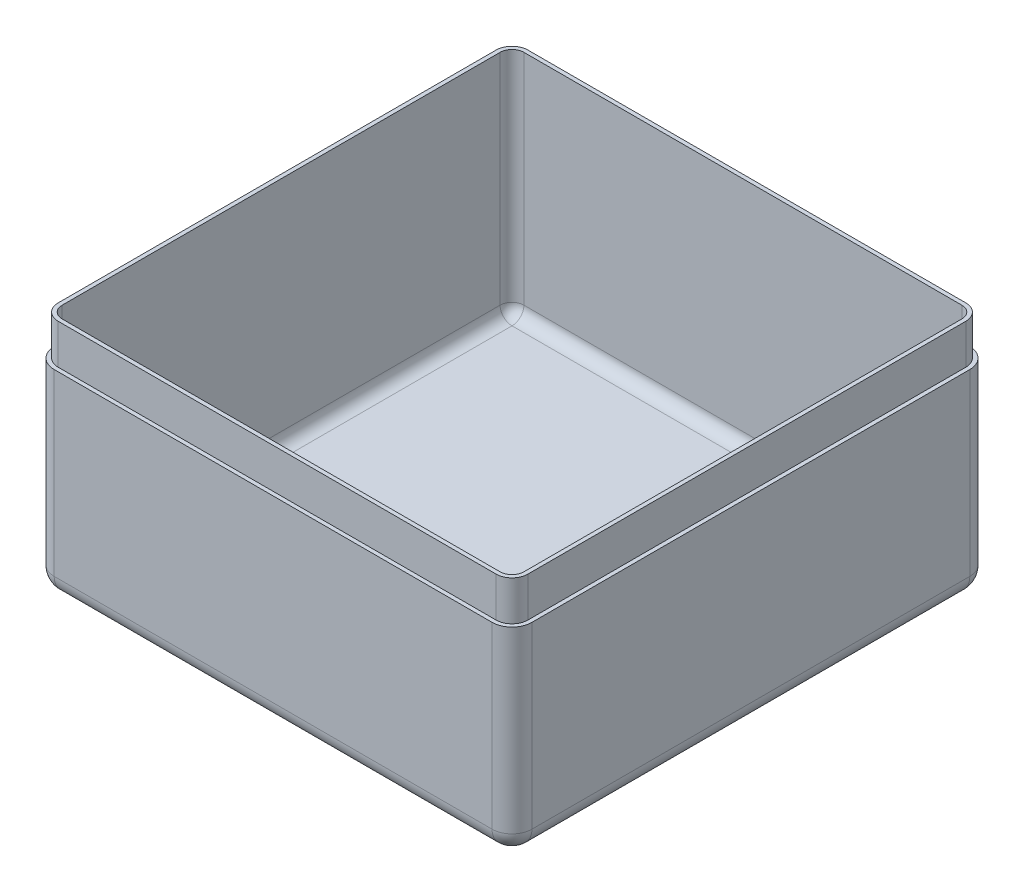
SolidWorks part; units mm, degrees
ref_plane "Front" through (0, 0, 0) normal (0, 0, 1) x (1, 0, 0)
ref_plane "Top" through (0, 0, 0) normal (0, 1, 0) x (1, 0, 0)
ref_plane "Right" through (0, 0, 0) normal (1, 0, 0) x (0, 0, -1)
sketch "Sketch1" plane through (0, 0, 0) normal (0, 1, 0) x (1, 0, 0)
  line L1 (0, 0) -> (60, 0)
  line L2 (0, 0) -> (0, 60)
  line L3 (0, 60) -> (60, 60)
  line L4 (60, 0) -> (60, 60)
  dimension "D1" = 60
  dimension "D2" = 60
extrude "Boss-Extrude1" add sketch "Sketch1" along normal blind 25
fillet "Fillet1" radius 2.5 8 edges at (30, 0, 0) (60, 0, -30) (30, 0, -60) (0, 0, -30) (0, 12.5, -60) (60, 12.5, -60) (60, 12.5, 0) (0, 12.5, 0)
shell "Shell1" thickness 1
sketch "Sketch5" plane through (0, 25, 0) normal (0, 1, 0) x (1, 0, 0)
  line L8 (57.5, 59) -> (2.5, 59)
  line L9 (1, 57.5) -> (1, 2.5)
  line L10 (2.5, 1) -> (57.5, 1)
  line L11 (59, 2.5) -> (59, 57.5)
  line L12 (57.5, 59) -> (2.5, 59)
  line L13 (1, 57.5) -> (1, 2.5)
  line L14 (2.5, 1) -> (57.5, 1)
  line L15 (59, 2.5) -> (59, 57.5)
  line L20 (57.5, 59.5) -> (2.5, 59.5)
  line L21 (0.5, 57.5) -> (0.5, 2.5)
  line L22 (2.5, 0.5) -> (57.5, 0.5)
  line L23 (59.5, 2.5) -> (59.5, 57.5)
  line L24 (57.5, 59.5) -> (2.5, 59.5)
  line L25 (0.5, 57.5) -> (0.5, 2.5)
  line L26 (2.5, 0.5) -> (57.5, 0.5)
  line L27 (59.5, 2.5) -> (59.5, 57.5)
  arc A8 (2.5, 59) -> (1, 57.5) centre (2.5, 57.5) ccw
  arc A9 (1, 2.5) -> (2.5, 1) centre (2.5, 2.5) ccw
  arc A10 (57.5, 1) -> (59, 2.5) centre (57.5, 2.5) ccw
  arc A11 (59, 57.5) -> (57.5, 59) centre (57.5, 57.5) ccw
  arc A12 (2.5, 59) -> (1, 57.5) centre (2.5, 57.5) ccw
  arc A13 (1, 2.5) -> (2.5, 1) centre (2.5, 2.5) ccw
  arc A14 (57.5, 1) -> (59, 2.5) centre (57.5, 2.5) ccw
  arc A15 (59, 57.5) -> (57.5, 59) centre (57.5, 57.5) ccw
  arc A20 (2.5, 59.5) -> (0.5, 57.5) centre (2.5, 57.5) ccw
  arc A21 (0.5, 2.5) -> (2.5, 0.5) centre (2.5, 2.5) ccw
  arc A22 (57.5, 0.5) -> (59.5, 2.5) centre (57.5, 2.5) ccw
  arc A23 (59.5, 57.5) -> (57.5, 59.5) centre (57.5, 57.5) ccw
  arc A24 (2.5, 59.5) -> (0.5, 57.5) centre (2.5, 57.5) ccw
  arc A25 (0.5, 2.5) -> (2.5, 0.5) centre (2.5, 2.5) ccw
  arc A26 (57.5, 0.5) -> (59.5, 2.5) centre (57.5, 2.5) ccw
  arc A27 (59.5, 57.5) -> (57.5, 59.5) centre (57.5, 57.5) ccw
  dimension "D1" = 1
  dimension "D2" = 0.5
extrude "Boss-Extrude2" add sketch "Sketch5" along normal blind 5
sketch "Sketch3" plane through (0, 25, 0) normal (0, 1, 0) x (1, 0, 0)
  line L8 (57.5, 59.5) -> (2.5, 59.5)
  line L9 (0.5, 57.5) -> (0.5, 2.5)
  line L10 (2.5, 0.5) -> (57.5, 0.5)
  line L11 (59.5, 2.5) -> (59.5, 57.5)
  line L12 (57.5, 59.5) -> (2.5, 59.5)
  line L13 (0.5, 57.5) -> (0.5, 2.5)
  line L14 (2.5, 0.5) -> (57.5, 0.5)
  line L15 (59.5, 2.5) -> (59.5, 57.5)
  line L20 (57.5, 59) -> (2.5, 59)
  line L21 (1, 57.5) -> (1, 2.5)
  line L22 (2.5, 1) -> (57.5, 1)
  line L23 (59, 2.5) -> (59, 57.5)
  line L24 (57.5, 59) -> (2.5, 59)
  line L25 (1, 57.5) -> (1, 2.5)
  line L26 (2.5, 1) -> (57.5, 1)
  line L27 (59, 2.5) -> (59, 57.5)
  arc A8 (2.5, 59.5) -> (0.5, 57.5) centre (2.5, 57.5) ccw
  arc A9 (0.5, 2.5) -> (2.5, 0.5) centre (2.5, 2.5) ccw
  arc A10 (57.5, 0.5) -> (59.5, 2.5) centre (57.5, 2.5) ccw
  arc A11 (59.5, 57.5) -> (57.5, 59.5) centre (57.5, 57.5) ccw
  arc A12 (2.5, 59.5) -> (0.5, 57.5) centre (2.5, 57.5) ccw
  arc A13 (0.5, 2.5) -> (2.5, 0.5) centre (2.5, 2.5) ccw
  arc A14 (57.5, 0.5) -> (59.5, 2.5) centre (57.5, 2.5) ccw
  arc A15 (59.5, 57.5) -> (57.5, 59.5) centre (57.5, 57.5) ccw
  arc A20 (2.5, 59) -> (1, 57.5) centre (2.5, 57.5) ccw
  arc A21 (1, 2.5) -> (2.5, 1) centre (2.5, 2.5) ccw
  arc A22 (57.5, 1) -> (59, 2.5) centre (57.5, 2.5) ccw
  arc A23 (59, 57.5) -> (57.5, 59) centre (57.5, 57.5) ccw
  arc A24 (2.5, 59) -> (1, 57.5) centre (2.5, 57.5) ccw
  arc A25 (1, 2.5) -> (2.5, 1) centre (2.5, 2.5) ccw
  arc A26 (57.5, 1) -> (59, 2.5) centre (57.5, 2.5) ccw
  arc A27 (59, 57.5) -> (57.5, 59) centre (57.5, 57.5) ccw
  dimension "D1" = 0.5
  dimension "D2" = 1
